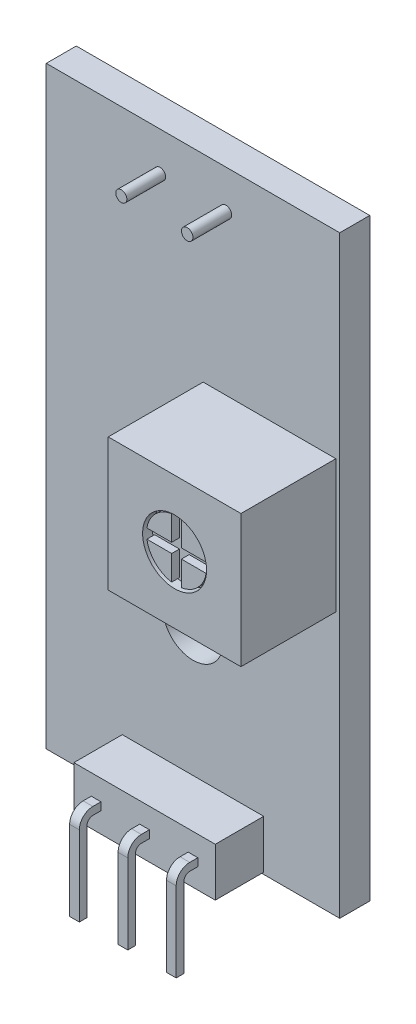
SolidWorks part; units mm, degrees
ref_plane "Plano frontal" through (0, 0, 0) normal (0, 0, 1) x (1, 0, 0)
ref_plane "Plano superior" through (0, 0, 0) normal (0, 1, 0) x (1, 0, 0)
ref_plane "Plano direito" through (0, 0, 0) normal (1, 0, 0) x (0, 0, -1)
sketch "Esboço1" plane through (0, 0, 0) normal (0, 0, 1) x (1, 0, 0)
  line L0 (0, -15.325) -> (0, -4.475) construction
  line L1 (7.575, 15.325) -> (-7.575, 15.325)
  line L2 (7.575, 15.325) -> (7.575, -15.325)
  line L3 (7.575, -15.325) -> (-7.575, -15.325)
  line L4 (-7.575, 15.325) -> (-7.575, -15.325)
  line L5 (7.575, 15.325) -> (-7.575, -15.325) construction
  line L6 (7.575, -15.325) -> (-7.575, 15.325) construction
  circle A0 centre (0, -6.025) radius 1.55
  point P0 (0, 0)
  dimension "D4" = 3.1
  dimension "D1" = 15.15
  dimension "D2" = 30.65
  dimension "D3" = 10.85
extrude "Ressalto-extrusão1" add sketch "Esboço1" along normal blind 1.55
sketch "Esboço2" plane through (0, 0, 0) normal (0, 0, 1) x (1, 0, 0)
  line L0 (7.575, -15.325) -> (7.575, 15.325) construction
  line L1 (7.375, 5.125) -> (0.525, 5.125)
  line L2 (7.375, 5.125) -> (7.375, -1.725)
  line L3 (7.375, -1.725) -> (0.525, -1.725)
  line L4 (0.525, 5.125) -> (0.525, -1.725)
  line L5 (-7.575, -15.325) -> (7.575, -15.325) construction
  dimension "D1" = 6.85
  dimension "D2" = 6.85
  dimension "D3" = 0.2
  dimension "D4" = 20.45
extrude "Ressalto-extrusão2" add sketch "Esboço2" along normal blind 6.45
sketch "Esboço3" plane through (0, 0, 6.45) normal (0, 0, 1) x (1, 0, 0)
  line L0 (0.525, -1.725) -> (7.375, 5.125) construction
  line L6 (3.7, 1.95) -> (2.4203, 1.95)
  line L7 (5.4797, 1.45) -> (4.2, 1.45)
  line L13 (5.4797, 1.95) -> (4.2, 1.95)
  line L15 (3.7, 1.45) -> (3.7, 0.1703)
  line L16 (4.2, 1.45) -> (4.2, 0.1703)
  line L19 (3.7, 3.2297) -> (3.7, 1.95)
  line L21 (4.2, 3.2297) -> (4.2, 1.95)
  line L22 (3.7, 1.45) -> (2.4203, 1.45)
  circle A0 centre (3.95, 1.7) radius 1.65
  arc A5 (5.4797, 1.95) -> (4.2, 3.2297) centre (3.95, 1.7) ccw
  circle A6 centre (3.95, 1.7) radius 1.55 construction
  arc A7 (2.4203, 1.45) -> (3.7, 0.1703) centre (3.95, 1.7) ccw
  arc A8 (4.2, 0.1703) -> (5.4797, 1.45) centre (3.95, 1.7) ccw
  arc A9 (3.7, 3.2297) -> (2.4203, 1.95) centre (3.95, 1.7) ccw
  point P7 (3.95, 1.7)
  dimension "D1" = 3.3
  dimension "D2" = 0.1
extrude "Corte-extrusão1" cut sketch "Esboço3" against normal blind 0.5
sketch "Esboço4" plane through (0, 0, 0) normal (0, 0, 1) x (1, 0, 0)
  line L2 (-3.65, -15.225) -> (-3.65, -12.725)
  line L3 (-3.65, -12.725) -> (3.65, -12.725)
  line L4 (3.65, -15.225) -> (3.65, -12.725)
  line L5 (0, -15.225) -> (0, -14.5169) construction
  line L6 (0, -15.225) -> (0, -11.5262) construction
  line L7 (-3.65, -15.225) -> (3.65, -15.225)
  line L8 (-7.575, -15.325) -> (7.575, -15.325) construction
  dimension "D1" = 7.3
  dimension "D2" = 0.1
  dimension "D3" = 2.5
extrude "Ressalto-extrusão3" add sketch "Esboço4" along normal blind 4.05
ref_plane "Plano1" through (0, 16.325, 0) normal (0, 1, 0) x (1, 0, 0)
sketch "Esboço9" plane through (0, 0, 6.45) normal (0, 0, 1) x (1, 0, 0)
  circle A1 centre (3.95, 1.7) radius 1.55
sketch "Esboço11" plane through (-3.65, 0, 0) normal (-1, 0, 0) x (0, 0, 1)
  line L0 (4.05, -13.975) -> (4.4674, -13.975) construction
  line L1 (4.05, -12.725) -> (4.05, -15.225) construction
  line L2 (4.9674, -14.475) -> (4.9674, -18.5951) construction
  line L3 (4.05, -14.175) -> (4.4674, -14.175)
  line L4 (4.7674, -14.475) -> (4.7674, -18.5951)
  line L5 (4.05, -13.775) -> (4.4674, -13.775)
  line L6 (5.1674, -14.475) -> (5.1674, -18.5951)
  line L7 (4.05, -13.775) -> (4.05, -14.175)
  line L8 (4.7674, -18.5951) -> (5.1674, -18.5951)
  arc A0 (4.4674, -13.975) -> (4.9674, -14.475) centre (4.4674, -14.475) cw construction
  arc A1 (4.4674, -14.175) -> (4.7674, -14.475) centre (4.4674, -14.475) cw
  arc A2 (4.4674, -13.775) -> (5.1674, -14.475) centre (4.4674, -14.475) cw
  dimension "D1" = 0.5
  dimension "D2" = 0.2
  dimension "D3" = 0.2
sketch "Esboço12" plane through (0, 0, 4.05) normal (0, 0, 1) x (1, 0, 0)
  line L0 (0, -12.725) -> (0, -12.2965) construction
  line L1 (-4.098, -13.3768) -> (-2.75, -13.3768)
  line L2 (-4.098, -13.3768) -> (-4.098, -19.3679)
  line L3 (-4.098, -19.3679) -> (-2.75, -19.3679)
  line L4 (-2.75, -13.3768) -> (-2.75, -19.3679)
  line L5 (3.7485, -13.3768) -> (2.75, -13.3768)
  line L6 (3.7485, -13.3768) -> (3.7485, -19.3679)
  line L7 (3.7485, -19.3679) -> (2.75, -19.3679)
  line L8 (2.75, -13.3768) -> (2.75, -19.3679)
  line L9 (-2.25, -13.3768) -> (-0.25, -13.3768)
  line L10 (-2.25, -13.3768) -> (-2.25, -19.3679)
  line L11 (-2.25, -19.3679) -> (-0.25, -19.3679)
  line L12 (-0.25, -13.3768) -> (-0.25, -19.3679)
  line L13 (2.25, -13.3768) -> (0.25, -13.3768)
  line L14 (2.25, -13.3768) -> (2.25, -19.3679)
  line L15 (2.25, -19.3679) -> (0.25, -19.3679)
  line L16 (0.25, -13.3768) -> (0.25, -19.3679)
  line L17 (3.65, -12.725) -> (-3.65, -12.725) construction
  line L18 (-0.25, -13.3768) -> (0.25, -13.3768) construction
  line L19 (0, -13.3768) -> (0, -14.2114) construction
  dimension "D1" = 0.5
  dimension "D2" = 0.5
  dimension "D3" = 0.5
  dimension "D4" = 2
  dimension "D5" = 2
extrude "Ressalto-extrusão5" add sketch "Esboço11" against normal up to vertex (7.3985 mm away) contours L6 L8 L4 A1 L3 L7 L5 A2 up to point (3.7485, -13.3768, 4.05)
extrude "Corte-extrusão2" cut sketch "Esboço12" along normal blind 10 contours L11 L12 L9 L10
extrude "Corte-extrusão3" cut sketch "Esboço9" against normal blind 0.1
ref_plane "Plano2" through (0, 22.325, 0) normal (0, 1, 0) x (1, 0, 0)
sketch "Esboço14" plane through (0, 22.325, 0) normal (0, 1, 0) x (1, 0, 0)
  line L0 (-1.4465, -0.9) -> (1.4465, -0.9) construction
  line L1 (-1.4465, -5.1) -> (1.4465, -5.1) construction
  line L2 (0, 0) -> (0, -3) construction
  circle A0 centre (-1.7, -3) radius 0.2856 construction
  circle A1 centre (1.7, -3) radius 0.2972 construction
  arc A2 (1.4465, -5.1) -> (1.4465, -0.9) centre (0, -3) ccw construction
  arc A3 (-1.4465, -0.9) -> (-1.4465, -5.1) centre (0, -3) ccw construction
  point P0 (0, -3)
  dimension "D1" = 3.4
  dimension "D2" = 1.7
  dimension "D3" = 3
ref_plane "Plano3" through (-1.7, 0, 0) normal (-1, 0, 0) x (0, 0, 1)
ref_plane "Plano4" through (0, 0, 0) normal (-1, 0, 0) x (0, 0, 1)
sketch "Esboço15" plane through (0, 0, 1.55) normal (0, 0, 1) x (1, 0, 0)
  line L0 (-1.7, 13.325) -> (1.7, 13.325) construction
  line L1 (0, 15.325) -> (0, 13.325) construction
  line L2 (7.575, 15.325) -> (-7.575, 15.325) construction
  circle A0 centre (1.7, 13.325) radius 0.2972
  circle A1 centre (-1.7, 13.325) radius 0.2856
  point P9 (0, 13.325)
  dimension "D2" = 0.5713
  dimension "D3" = 0.5944
  dimension "D1" = 3.4
  dimension "D4" = 2
extrude "Ressalto-extrusão6" add sketch "Esboço15" along normal blind 2
